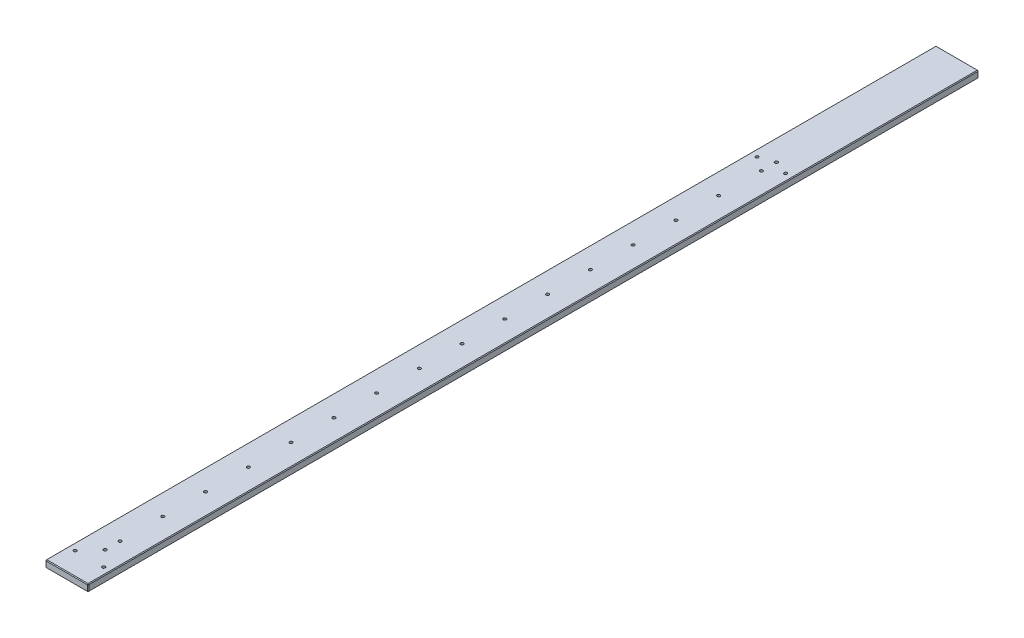
SolidWorks part; units mm, degrees
ref_plane "前视基准面" through (0, 0, 0) normal (0, 0, 1) x (1, 0, 0)
ref_plane "上视基准面" through (0, 0, 0) normal (0, 1, 0) x (1, 0, 0)
ref_plane "右视基准面" through (0, 0, 0) normal (1, 0, 0) x (0, 0, -1)
sketch "草图1" plane through (0, 0, 0) normal (0, 0, 1) x (1, 0, 0)
  line L1 (-30, -5) -> (30, -5)
  line L2 (-30, -5) -> (-30, 5)
  line L3 (-30, 5) -> (30, 5)
  line L4 (30, -5) -> (30, 5)
  line L5 (-30, -5) -> (30, 5) construction
  line L6 (-30, 5) -> (30, -5) construction
  point P0 (0, 0)
  dimension "D1" = 60
  dimension "D2" = 10
extrude "凸台-拉伸2" add sketch "草图1" along normal blind 1250
sketch "草图2" plane through (0, -5, 0) normal (0, -1, 0) x (1, 0, 0)
  point P0 (0, 1175)
  point P1 (0, 1115)
  point P3 (0, 1055)
  point P5 (0, 995)
  point P7 (0, 935)
  point P9 (0, 875)
  point P11 (0, 815)
  point P13 (0, 755)
  point P15 (0, 695)
  point P17 (0, 635)
  point P19 (0, 515)
  point P21 (0, 455)
  point P23 (0, 395)
  point P25 (0, 335)
  point P27 (0, 275)
  point P29 (0, 575)
hole_wizard "M5 螺纹孔2" positions "草图3" profile "草图4" tap size "M5" standard "ISO" end condition through all
sketch "草图3" plane through (0, -5, 0) normal (0, -1, 0) x (-1, 0, 0)
  point P0 (0, -275)
  point P3 (0, -335)
  point P6 (0, -395)
  point P9 (0, -455)
  point P12 (0, -515)
  point P15 (0, -575)
  point P18 (0, -635)
  point P21 (0, -695)
  point P24 (0, -755)
  point P27 (0, -815)
  point P30 (0, -875)
  point P33 (0, -935)
  point P36 (0, -995)
  point P39 (0, -1055)
  point P42 (0, -1115)
  point P45 (0, -1175)
sketch "草图4" plane through (0, -5, 275) normal (1, 0, 0) x (0, 0, -1)
  line L0 (0, 0) -> (0, 10)
  line L1 (0, 10) -> (2.1, 10)
  line L2 (2.1, 10) -> (2.1, 0)
  line L5 (2.1, 0) -> (0, 0)
  line L11 (0, -6.35) -> (0, 107.95) construction
  dimension "通孔螺纹孔钻头直径" = 4.2
  dimension "通孔螺纹孔钻头深度" = 10
cosmetic thread "孔螺蚊线1" parameters "D2"=5
cosmetic thread "孔螺蚊线2" parameters "D2"=5
cosmetic thread "孔螺蚊线3" parameters "D2"=5
cosmetic thread "孔螺蚊线4" parameters "D2"=5
cosmetic thread "孔螺蚊线5" parameters "D2"=5
cosmetic thread "孔螺蚊线6" parameters "D2"=5
cosmetic thread "孔螺蚊线7" parameters "D2"=5
cosmetic thread "孔螺蚊线8" parameters "D2"=5
cosmetic thread "孔螺蚊线9" parameters "D2"=5
cosmetic thread "孔螺蚊线10" parameters "D2"=5
cosmetic thread "孔螺蚊线11" parameters "D2"=5
cosmetic thread "孔螺蚊线12" parameters "D2"=5
cosmetic thread "孔螺蚊线13" parameters "D2"=5
cosmetic thread "孔螺蚊线14" parameters "D2"=5
cosmetic thread "孔螺蚊线15" parameters "D2"=5
cosmetic thread "孔螺蚊线16" parameters "D2"=5
sketch "草图5" plane through (0, -5, 0) normal (0, -1, 0) x (1, 0, 0)
  line L0 (0, 1190) -> (0, 1196) construction
  line L1 (7.2307, 1190) -> (-7.2307, 1190) construction
  line L2 (0, 260) -> (0, 254) construction
  line L3 (7.2307, 260) -> (-7.2307, 260) construction
  dimension "D1" = 6
  dimension "D2" = 6
hole_wizard "M5 螺纹孔1" positions "草图6" profile "草图7" tap size "M5" standard "ISO" end condition through all
sketch "草图6" plane through (0, -5, 0) normal (0, -1, 0) x (-1, 0, 0)
  point P0 (0, -254)
  point P3 (0, -1196)
sketch "草图7" plane through (0, -5, 254) normal (1, 0, 0) x (0, 0, -1)
  line L0 (0, 0) -> (0, 10)
  line L1 (0, 10) -> (2.1, 10)
  line L2 (2.1, 10) -> (2.1, 0)
  line L5 (2.1, 0) -> (0, 0)
  line L11 (0, -6.35) -> (0, 107.95) construction
  dimension "通孔螺纹孔钻头直径" = 4.2
  dimension "通孔螺纹孔钻头深度" = 10
cosmetic thread "孔螺蚊线17" parameters "D2"=5
cosmetic thread "孔螺蚊线18" parameters "D2"=5
chamfer "倒角1" distance 1 angle 45 12 edges at (0, 5, 0) (0, -5, 0) (30, -5, 625) (30, 0, 0) (30, 5, 625) (-30, 5, 625) (-30, 0, 0) (-30, -5, 625) (0, -5, 1250) (-30, 0, 1250) (0, 5, 1250) (30, 0, 1250)
sketch "草图8" plane through (0, -5, 0) normal (0, -1, 0) x (1, 0, 0)
  line L2 (-22.75, 261) -> (-17.25, 261)
  line L3 (17.25, 261) -> (22.75, 261)
hole_wizard "M5 螺纹孔3" positions "草图9" profile "草图10" tap size "M5" standard "GB" end condition through all
sketch "草图9" plane through (0, -5, 0) normal (0, -1, 0) x (-1, 0, 0)
  line L0 (-17.25, -261) -> (-22.75, -261) construction
  line L1 (22.75, -261) -> (17.25, -261) construction
  point P0 (-20, -261)
  point P4 (20, -261)
  point P17 (0, 0)
  point P18 (0, 0)
sketch "草图10" plane through (20, -5, 261) normal (1, 0, 0) x (0, 0, -1)
  line L0 (0, 0) -> (0, 10)
  line L1 (0, 10) -> (2.1, 10)
  line L2 (2.1, 10) -> (2.1, 0)
  line L5 (2.1, 0) -> (0, 0)
  line L11 (0, -6.35) -> (0, 107.95) construction
  dimension "通孔螺纹孔钻头直径" = 4.2
  dimension "通孔螺纹孔钻头深度" = 10
cosmetic thread "孔螺蚊线21" parameters "D2"=5
cosmetic thread "孔螺蚊线22" parameters "D2"=5
sketch "草图11" plane through (0, -5, 0) normal (0, -1, 0) x (1, 0, 0)
  line L0 (-17.25, 1218) -> (-22.75, 1218) construction
  line L1 (17.25, 1218) -> (22.75, 1218) construction
hole_wizard "M5 螺纹孔4" positions "草图12" profile "草图13" tap size "M5" standard "GB" end condition through all
sketch "草图12" plane through (0, 5, 0) normal (0, 1, 0) x (1, 0, 0)
  line L0 (17.25, -1218) -> (22.75, -1218) construction
  line L1 (-17.25, -1218) -> (-22.75, -1218) construction
  point P0 (20, -1218)
  point P4 (-20, -1218)
sketch "草图13" plane through (20, 5, 1218) normal (1, 0, 0) x (0, 0, 1)
  line L0 (0, 0) -> (0, 10)
  line L1 (0, 10) -> (2.1, 10)
  line L2 (2.1, 10) -> (2.1, 0)
  line L5 (2.1, 0) -> (0, 0)
  line L11 (0, -6.35) -> (0, 107.95) construction
  dimension "通孔螺纹孔钻头直径" = 4.2
  dimension "通孔螺纹孔钻头深度" = 10
cosmetic thread "孔螺蚊线23" parameters "D2"=5
cosmetic thread "孔螺蚊线24" parameters "D2"=5
